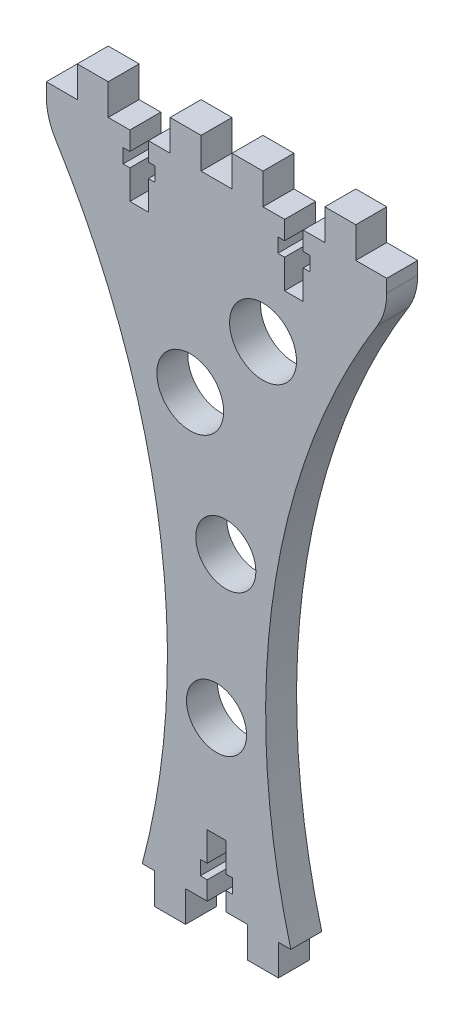
SolidWorks part; units mm, degrees
ref_plane "Plan de face" through (0, 0, 0) normal (0, 0, 1) x (1, 0, 0)
ref_plane "Plan de dessus" through (0, 0, 0) normal (0, 1, 0) x (1, 0, 0)
ref_plane "Plan de droite" through (0, 0, 0) normal (1, 0, 0) x (0, 0, -1)
sketch "Esquisse1" plane through (0, 0, 0) normal (0, 0, 1) x (1, 0, 0)
  line L0 (12, 0) -> (27.5, 96.6497) construction
  line L1 (0, 0) -> (0, -30.9586) construction
  line L2 (-10, 0) -> (-12, 0)
  line L3 (-27.5, 96.6497) -> (-27.5, 101.6497)
  line L4 (-12, 0) -> (-27.5, 96.6497) construction
  line L5 (-2.5, 101.6497) -> (2.5, 101.6497)
  line L6 (10, 0) -> (12, 0)
  line L8 (27.5, 96.6497) -> (27.5, 101.6497)
  line L9 (27.5, 101.6497) -> (22.5, 101.6497)
  line L10 (-22.5, 101.6497) -> (-27.5, 101.6497)
  circle A1 centre (7.5129, 82.7881) radius 5.4066
  circle A5 centre (-4.2453, 69.8273) radius 5.3954
  circle A6 centre (1.5002, 50.052) radius 4.8547
  circle A7 centre (0, 26.4018) radius 4.8548
  arc A8 (-27.5, 96.6497) -> (-12, 0) centre (-127.9333, 30.9751) cw
  arc A9 (27.5, 96.6497) -> (12, 0) centre (127.9333, 30.9751) ccw
  point P1 (7.5129, 77.3098)
  point P16 (-3.7109, 64.4826)
  point P19 (2.5, 50.9873)
  point P20 (-4.2453, 69.8273)
  point P23 (7.5129, 82.7881)
  point P24 (0, 26.4018)
  point P31 (1.5002, 50.052)
  line B0 (-2.6, 3) -> (-2.6, 5.3)
  line B1 (1.5, 5.3) -> (1.5, 10)
  line B2 (-1.5, 10) -> (-1.5, 5.3)
  line B3 (-2.6, 5.3) -> (-1.5, 5.3)
  line B4 (0, 0) -> (0, 11.2208) construction
  line B5 (-1.5, 0) -> (-5, 0)
  line B6 (-5, -5) -> (-10, -5)
  line B7 (-10, -5) -> (-10, 0)
  line B8 (-5, -5) -> (-5, 0)
  line B9 (1.5, 0) -> (5, 0)
  line B10 (5, 0) -> (5, -5)
  line B11 (5, -5) -> (10, -5)
  line B12 (10, -5) -> (10, 0)
  line B13 (-1.5, 0) -> (1.5, 0) construction
  line B14 (1.5, 0) -> (1.5, 3)
  line B15 (1.5, 5.3) -> (2.6, 5.3)
  line B16 (2.6, 3) -> (1.5, 3)
  line B17 (1.5, 10) -> (-1.5, 10)
  line B18 (-1.5, 3) -> (-2.6, 3)
  line B19 (2.6, 5.3) -> (2.6, 3)
  line B20 (-1.5, 3) -> (-1.5, 0)
  line B21 (0, 10) -> (0, 0) construction
  line B22 (15.1, 98.6497) -> (15.1, 96.3497)
  line B23 (11, 96.3497) -> (11, 91.6497)
  line B24 (14, 91.6497) -> (14, 96.3497)
  line B25 (15.1, 96.3497) -> (14, 96.3497)
  line B26 (12.5, 101.6497) -> (12.5, 90.4289) construction
  line B27 (14, 101.6497) -> (17.5, 101.6497)
  line B28 (17.5, 106.6497) -> (22.5, 106.6497)
  line B29 (22.5, 106.6497) -> (22.5, 101.6497)
  line B30 (17.5, 106.6497) -> (17.5, 101.6497)
  line B31 (11, 101.6497) -> (7.5, 101.6497)
  line B32 (7.5, 101.6497) -> (7.5, 106.6497)
  line B33 (7.5, 106.6497) -> (2.5, 106.6497)
  line B34 (2.5, 106.6497) -> (2.5, 101.6497)
  line B35 (14, 101.6497) -> (11, 101.6497) construction
  line B36 (11, 101.6497) -> (11, 98.6497)
  line B37 (11, 96.3497) -> (9.9, 96.3497)
  line B38 (9.9, 98.6497) -> (11, 98.6497)
  line B39 (11, 91.6497) -> (14, 91.6497)
  line B40 (14, 98.6497) -> (15.1, 98.6497)
  line B41 (9.9, 96.3497) -> (9.9, 98.6497)
  line B42 (14, 98.6497) -> (14, 101.6497)
  line B43 (12.5, 91.6497) -> (12.5, 101.6497) construction
  line B44 (-15.1, 98.6497) -> (-15.1, 96.3497)
  line B45 (-11, 96.3497) -> (-11, 91.6497)
  line B46 (-14, 91.6497) -> (-14, 96.3497)
  line B47 (-15.1, 96.3497) -> (-14, 96.3497)
  line B48 (-12.5, 101.6497) -> (-12.5, 90.4289) construction
  line B49 (-14, 101.6497) -> (-17.5, 101.6497)
  line B50 (-17.5, 106.6497) -> (-22.5, 106.6497)
  line B51 (-22.5, 106.6497) -> (-22.5, 101.6497)
  line B52 (-17.5, 106.6497) -> (-17.5, 101.6497)
  line B53 (-11, 101.6497) -> (-7.5, 101.6497)
  line B54 (-7.5, 101.6497) -> (-7.5, 106.6497)
  line B55 (-7.5, 106.6497) -> (-2.5, 106.6497)
  line B56 (-2.5, 106.6497) -> (-2.5, 101.6497)
  line B57 (-14, 101.6497) -> (-11, 101.6497) construction
  line B58 (-11, 101.6497) -> (-11, 98.6497)
  line B59 (-11, 96.3497) -> (-9.9, 96.3497)
  line B60 (-9.9, 98.6497) -> (-11, 98.6497)
  line B61 (-11, 91.6497) -> (-14, 91.6497)
  line B62 (-14, 98.6497) -> (-15.1, 98.6497)
  line B63 (-9.9, 96.3497) -> (-9.9, 98.6497)
  line B64 (-14, 98.6497) -> (-14, 101.6497)
  line B65 (-12.5, 91.6497) -> (-12.5, 101.6497) construction
  dimension "D6" = 120
  dimension "D1" = 5
  dimension "D2" = 0
  dimension "D3" = 5
  dimension "D4" = 101.6497
  dimension "D5" = 2
  dimension "D7" = 5
sketch_block_instance "Insert M3 plots ep 5mm-1"
sketch_block "Insert M3 plots ep 5mm" parameters "D1"=10, "D2"=5, "D3"=5
sketch_block_instance "Decoupe Insert M3-4"
sketch_block "Decoupe Insert M3" parameters "D1"=5.2, "D2"=3, "D3"=2.3, "D4"=3, "D5"=10
sketch_block_instance "Insert M3 plots ep 5mm-3"
sketch_block_instance "Insert M3 plots ep 5mm-4"
extrude "Boss.-Extru.1" add sketch "Esquisse1" along normal blind 5
fillet "Congé1" radius 10 2 edges at (-27.5, 96.6497, 2.5) (27.5, 96.6497, 2.5)
